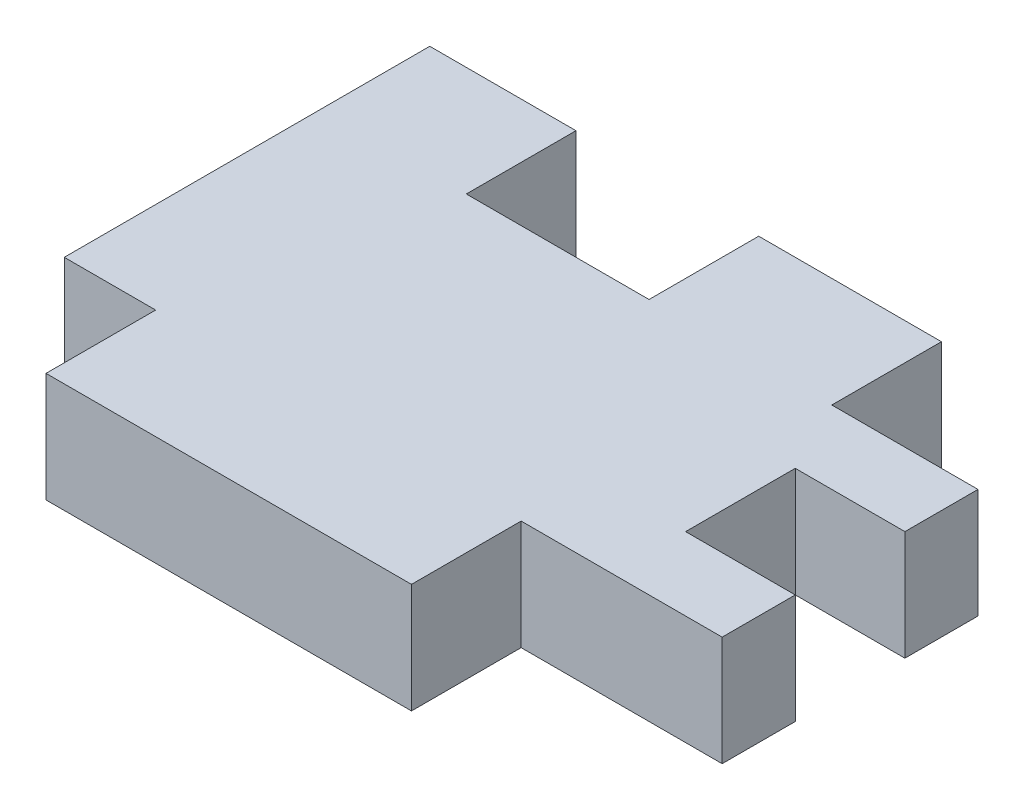
SolidWorks part; units mm, degrees
ref_plane "Alzado" through (0, 0, 0) normal (0, 0, 1) x (1, 0, 0)
ref_plane "Planta" through (0, 0, 0) normal (0, 1, 0) x (1, 0, 0)
ref_plane "Vista lateral" through (0, 0, 0) normal (1, 0, 0) x (0, 0, -1)
sketch "Croquis1" plane through (0, 0, 0) normal (0, 1, 0) x (1, 0, 0)
  line L0 (2.5, 0) -> (12.5, 0)
  line L1 (18, 3) -> (18, 5)
  line L2 (14, 13) -> (9, 13)
  line L3 (0, 13) -> (0, 3)
  line L5 (2.5, 0) -> (2.5, 3)
  line L6 (2.5, 3) -> (0, 3)
  line L7 (2.5, 0) -> (12.5, 0)
  line L8 (12.5, 0) -> (12.5, 3)
  line L9 (12.5, 3) -> (18, 3)
  line L10 (9, 13) -> (9, 10)
  line L11 (9, 10) -> (4, 10)
  line L12 (4, 10) -> (4, 13)
  line L13 (9, 10) -> (14, 10)
  line L14 (14, 10) -> (14, 13)
  line L15 (14, 10) -> (18, 10)
  line L17 (15, 6.5) -> (15, 8)
  line L18 (15, 8) -> (18, 8)
  line L19 (15, 6.5) -> (15, 5)
  line L20 (15, 5) -> (18, 5)
  line L21 (18, 8) -> (18, 10)
  line L22 (4, 13) -> (0, 13)
  dimension "D2" = 10
  dimension "D4" = 3
  dimension "D5" = 10
  dimension "D6" = 3
  dimension "D7" = 5
  dimension "D8" = 5
  dimension "D10" = 1.5
  dimension "D11" = 1.5
extrude "Saliente-Extruir1" add sketch "Croquis1" along normal blind 3 contours L12 L22 L3 L6 L5 L0 L8 L9 L1 L20 L19 L17 L18 L21 L15 L13 L11 | L13 L14 L2 L10
